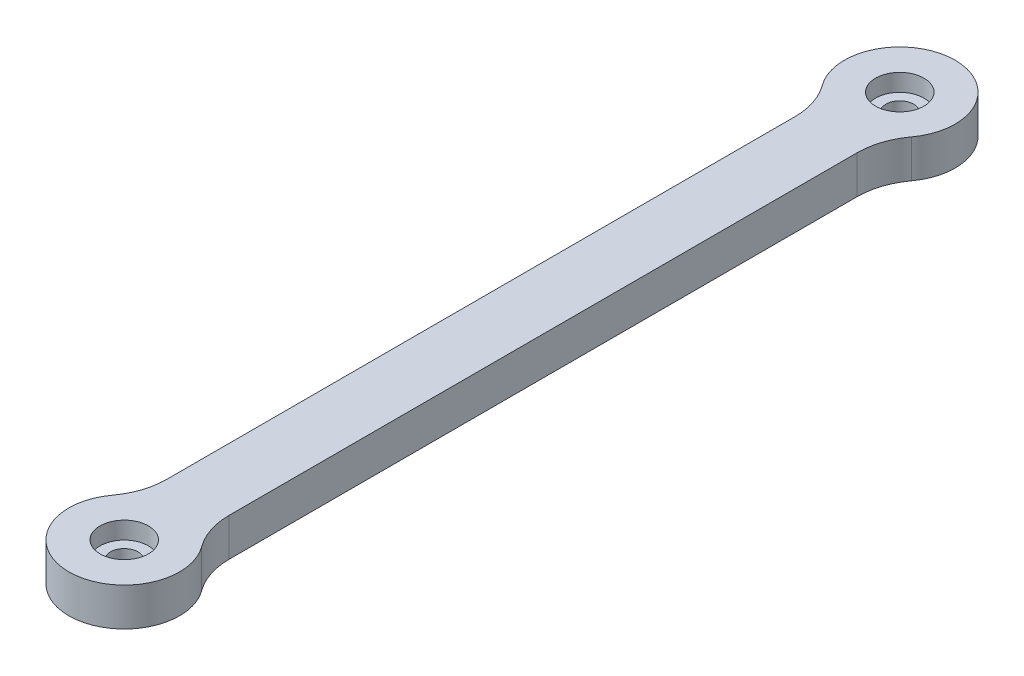
SolidWorks part; units mm, degrees
ref_plane "Ön Düzlem" through (0, 0, 0) normal (0, 0, 1) x (1, 0, 0)
ref_plane "Üst Düzlem" through (0, 0, 0) normal (0, 1, 0) x (1, 0, 0)
ref_plane "Sağ Düzlem" through (0, 0, 0) normal (1, 0, 0) x (0, 0, -1)
sketch "Sketch1" plane through (0, 0, 0) normal (0, 1, 0) x (1, 0, 0)
  line L0 (0, 56) -> (0, 48) construction
  line L1 (-4.5, 45.3346) -> (-4.5, -45.3346)
  line L2 (4.5, 45.3346) -> (4.5, -45.3346)
  line L3 (-4.5, 0) -> (4.5, 0) construction
  line L4 (-4.5, 56) -> (-4.5, 0) construction
  line L5 (0, 56) -> (0, 0) construction
  line L6 (4.5, 56) -> (4.5, 0) construction
  line L7 (0, -56) -> (0, -48) construction
  circle A0 centre (0, 56) radius 2
  arc A1 (6.4444, 51.2598) -> (-6.4444, 51.2598) centre (0, 56) ccw
  arc A2 (6.4444, 51.2598) -> (4.5, 45.3346) centre (14.5, 45.3346) ccw
  arc A3 (-4.5, 45.3346) -> (-6.4444, 51.2598) centre (-14.5, 45.3346) ccw
  arc A4 (-4.5, -45.3346) -> (-6.4444, -51.2598) centre (-14.5, -45.3346) cw
  arc A5 (6.4444, -51.2598) -> (4.5, -45.3346) centre (14.5, -45.3346) cw
  arc A6 (6.4444, -51.2598) -> (-6.4444, -51.2598) centre (0, -56) cw
  circle A7 centre (0, -56) radius 2
  dimension "D1" = 4
  dimension "D2" = 16
  dimension "D6" = 10
  dimension "D3" = 56
  dimension "D4" = 4.5
  dimension "D5" = 4.5
extrude "Boss-Extrude1" add sketch "Sketch1" along normal blind 5.5
sketch "Sketch2" plane through (0, 5.5, 0) normal (0, 1, 0) x (1, 0, 0)
  circle A0 centre (0, 56) radius 2 construction
  circle A1 centre (0, 56) radius 2
  circle A2 centre (0, 56) radius 3.5
  circle A3 centre (0, -56) radius 2 construction
  circle A4 centre (0, -56) radius 2
  circle A5 centre (0, -56) radius 3.5
extrude "Cut-Extrude1" cut sketch "Sketch2" against normal blind 2.5
